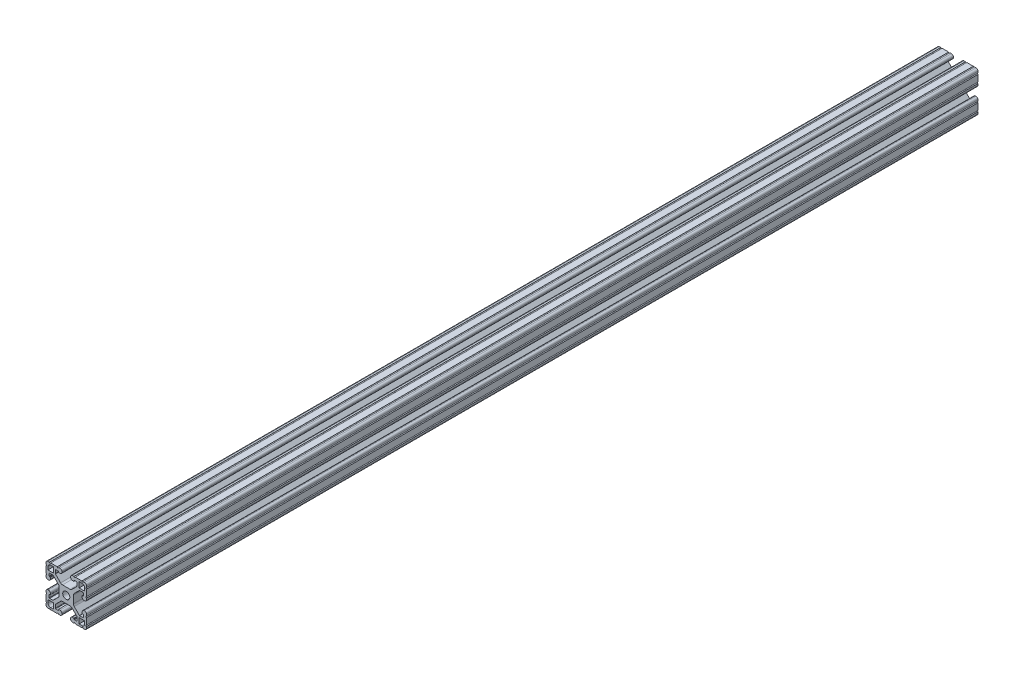
SolidWorks part; units mm, degrees
ref_plane "Front Plane" through (0, 0, 0) normal (0, 0, 1) x (1, 0, 0)
ref_plane "Top Plane" through (0, 0, 0) normal (0, 1, 0) x (1, 0, 0)
ref_plane "Right Plane" through (0, 0, 0) normal (1, 0, 0) x (0, 0, -1)
sketch "Sketch1" plane through (0, 0, 0) normal (0, 0, 1) x (1, 0, 0)
  line L0 (0, -19.05) -> (0, 19.05) construction
  line L1 (19.05, 0) -> (-19.05, 0) construction
  line L2 (4.064, 19.05) -> (-4.064, 19.05) construction
  line L3 (0, -6.7564) -> (0, 6.7564) construction
  line L4 (-4.064, 19.05) -> (-4.064, 14.986) construction
  line L5 (19.05, -10.287) -> (19.05, 10.287) construction
  line L6 (0, -3.3274) -> (0, 3.3274) construction
  line L7 (0, 0) -> (-19.05, 19.05) construction
  line L8 (-8.4474, 10.6026) -> (-10.6026, 8.4474) construction
  point P4 (0, 0)
  point P8 (0, 0)
  point P11 (0, 19.05)
  point P14 (0, 0)
  point P18 (19.05, 0)
  point P21 (0, 0)
  point P24 (-9.525, 9.525)
  point P26 (-9.525, 9.525)
  dimension "T-Slot Width" = 8.128
  dimension "Thickness" = 4.064
  dimension "Opening Width" = 20.574
  dimension "Slot Depth" = 12.2936
  dimension "Center Hole Diameter" = 6.6548
  dimension "Rail Height" = 38.1
  dimension "Rail Width" = 38.1
  dimension "D1" = 45
  dimension "Wall" = 3.048
sketch "Sketch2" plane through (0, 0, 0) normal (1, 0, 0) x (0, 0, -1)
  line L0 (-457.2, 0) -> (457.2, 0) construction
  line L1 (-381, -19.05) -> (-381, 19.05) construction
  line L2 (381, -19.05) -> (381, 19.05) construction
  line L3 (0, -19.05) -> (0, 19.05) construction
  point P4 (0, 0)
  point P7 (-381, 0)
  point P10 (381, 0)
  dimension "Length" = 914.4
  dimension "D1" = 76.2
  dimension "D2" = 76.2
sketch "Sketch3" plane through (0, 0, 0) normal (0, 0, 1) x (1, 0, 0)
  line L1 (19.05, -19.05) -> (-19.05, -19.05)
  line L2 (19.05, -19.05) -> (19.05, 19.05)
  line L3 (19.05, 19.05) -> (-19.05, 19.05)
  line L4 (-19.05, -19.05) -> (-19.05, 19.05)
  line L5 (19.05, -19.05) -> (-19.05, 19.05) construction
  line L6 (19.05, 19.05) -> (-19.05, -19.05) construction
  point P0 (0, 0)
extrude "Boss-Extrude1" add sketch "Sketch3" along normal blind 431.8 and the other way blind 406.4
sketch "Sketch4" plane through (0, 0, 431.8) normal (0, 0, 1) x (1, 0, 0)
  line L4 (4.064, 14.986) -> (4.064, 19.05)
  line L5 (7.239, 14.986) -> (4.064, 14.986)
  line L6 (19.05, 0) -> (-19.05, 0) construction
  line L7 (4.6011, 6.7564) -> (-4.6011, 6.7564)
  line L8 (-4.6011, 6.7564) -> (-10.287, 12.4423)
  line L37 (-19.05, 19.05) -> (-19.05, -19.05) construction
  line L38 (-19.05, -19.05) -> (19.05, -19.05) construction
  line L39 (-10.287, 12.4423) -> (-10.287, 16.002)
  line L40 (-10.287, 16.002) -> (-7.239, 16.002)
  line L41 (-7.239, 16.002) -> (-7.239, 14.986)
  line L42 (-7.239, 14.986) -> (-4.064, 14.986)
  line L43 (-4.064, 14.986) -> (-4.064, 19.05)
  line L44 (-4.064, 19.05) -> (4.064, 19.05)
  line L45 (0, 19.05) -> (0, 0) construction
  line L46 (-19.05, 19.05) -> (0, 0) construction
  line L47 (7.239, 16.002) -> (7.239, 14.986)
  line L48 (10.287, 16.002) -> (7.239, 16.002)
  line L49 (10.287, 12.4423) -> (10.287, 16.002)
  line L50 (4.6011, 6.7564) -> (10.287, 12.4423)
  line L51 (-19.05, 0) -> (19.05, 0) construction
  line L52 (4.6011, -6.7564) -> (10.287, -12.4423)
  line L53 (10.287, -12.4423) -> (10.287, -16.002)
  line L54 (10.287, -16.002) -> (7.239, -16.002)
  line L55 (7.239, -16.002) -> (7.239, -14.986)
  line L56 (-4.064, -19.05) -> (4.064, -19.05)
  line L57 (-4.064, -14.986) -> (-4.064, -19.05)
  line L58 (-7.239, -14.986) -> (-4.064, -14.986)
  line L59 (-7.239, -16.002) -> (-7.239, -14.986)
  line L60 (-10.287, -16.002) -> (-7.239, -16.002)
  line L61 (-10.287, -12.4423) -> (-10.287, -16.002)
  line L62 (-4.6011, -6.7564) -> (-10.287, -12.4423)
  line L63 (4.6011, -6.7564) -> (-4.6011, -6.7564)
  line L64 (7.239, -14.986) -> (4.064, -14.986)
  line L65 (4.064, -14.986) -> (4.064, -19.05)
  line L66 (-6.7564, -4.6011) -> (-12.4423, -10.287)
  line L67 (-12.4423, -10.287) -> (-16.002, -10.287)
  line L68 (-16.002, -10.287) -> (-16.002, -7.239)
  line L69 (-16.002, -7.239) -> (-14.986, -7.239)
  line L70 (-19.05, 4.064) -> (-19.05, -4.064)
  line L71 (-14.986, 4.064) -> (-19.05, 4.064)
  line L72 (-14.986, 7.239) -> (-14.986, 4.064)
  line L73 (-16.002, 7.239) -> (-14.986, 7.239)
  line L74 (-16.002, 10.287) -> (-16.002, 7.239)
  line L75 (-12.4423, 10.287) -> (-16.002, 10.287)
  line L76 (-6.7564, 4.6011) -> (-12.4423, 10.287)
  line L77 (-6.7564, -4.6011) -> (-6.7564, 4.6011)
  line L78 (-14.986, -7.239) -> (-14.986, -4.064)
  line L79 (-14.986, -4.064) -> (-19.05, -4.064)
  line L80 (14.986, -4.064) -> (19.05, -4.064)
  line L81 (14.986, -7.239) -> (14.986, -4.064)
  line L82 (6.7564, -4.6011) -> (6.7564, 4.6011)
  line L83 (6.7564, 4.6011) -> (12.4423, 10.287)
  line L84 (12.4423, 10.287) -> (16.002, 10.287)
  line L85 (16.002, 10.287) -> (16.002, 7.239)
  line L86 (16.002, 7.239) -> (14.986, 7.239)
  line L87 (14.986, 7.239) -> (14.986, 4.064)
  line L88 (14.986, 4.064) -> (19.05, 4.064)
  line L89 (19.05, 4.064) -> (19.05, -4.064)
  line L90 (16.002, -7.239) -> (14.986, -7.239)
  line L91 (16.002, -10.287) -> (16.002, -7.239)
  line L92 (12.4423, -10.287) -> (16.002, -10.287)
  line L93 (6.7564, -4.6011) -> (12.4423, -10.287)
  line L94 (19.05, -19.05) -> (19.05, 19.05) construction
  line L95 (12.065, 17.272) -> (17.272, 17.272)
  line L96 (12.065, 17.272) -> (12.065, 12.065)
  line L97 (12.065, 12.065) -> (17.272, 12.065)
  line L98 (17.272, 17.272) -> (17.272, 12.065)
  line L99 (19.05, 19.05) -> (-19.05, 19.05) construction
  line L100 (17.272, -17.272) -> (17.272, -12.065)
  line L101 (12.065, -17.272) -> (17.272, -17.272)
  line L102 (12.065, -17.272) -> (12.065, -12.065)
  line L103 (12.065, -12.065) -> (17.272, -12.065)
  line L104 (-17.272, 17.272) -> (-17.272, 12.065)
  line L105 (-12.065, 12.065) -> (-17.272, 12.065)
  line L106 (-12.065, 17.272) -> (-12.065, 12.065)
  line L107 (-12.065, 17.272) -> (-17.272, 17.272)
  line L108 (-12.065, -12.065) -> (-17.272, -12.065)
  line L109 (-12.065, -17.272) -> (-12.065, -12.065)
  line L110 (-12.065, -17.272) -> (-17.272, -17.272)
  line L111 (-17.272, -17.272) -> (-17.272, -12.065)
  circle A5 centre (0, 0) radius 3.3274
  point P21 (0, 6.7564)
  point P23 (0, -6.7564)
  point P38 (-6.7564, 0)
  point P53 (6.7564, 0)
  dimension "D1" = 20.574
  dimension "D3" = 3.048
  dimension "D4" = 3.048
  dimension "D5" = 1.778
  dimension "D6" = 1.778
  dimension "D7" = 1.778
extrude "Cut-Extrude1" cut sketch "Sketch4" against normal through all
sketch "Sketch5" plane through (0, 0, 431.8) normal (0, 0, 1) x (1, 0, 0)
  line L4 (-4.064, 19.05) -> (-19.05, 19.05) construction
  line L26 (-19.05, 19.05) -> (-19.05, 4.064) construction
  line L27 (-15.875, 19.05) -> (-14.605, 19.05)
  line L28 (-8.509, 19.05) -> (-7.239, 19.05)
  line L29 (-19.05, 15.875) -> (-19.05, 14.605)
  line L30 (-19.05, 8.509) -> (-19.05, 7.239)
  line L31 (8.509, 19.05) -> (7.239, 19.05)
  line L32 (15.875, 19.05) -> (14.605, 19.05)
  line L33 (19.05, 15.875) -> (19.05, 14.605)
  line L34 (19.05, 8.509) -> (19.05, 7.239)
  line L35 (19.05, -8.509) -> (19.05, -7.239)
  line L36 (19.05, -15.875) -> (19.05, -14.605)
  line L37 (15.875, -19.05) -> (14.605, -19.05)
  line L38 (8.509, -19.05) -> (7.239, -19.05)
  line L39 (-8.509, -19.05) -> (-7.239, -19.05)
  line L40 (-15.875, -19.05) -> (-14.605, -19.05)
  line L41 (-19.05, -15.875) -> (-19.05, -14.605)
  line L42 (-19.05, -8.509) -> (-19.05, -7.239)
  line L43 (19.05, 19.05) -> (4.064, 19.05) construction
  line L44 (19.05, 4.064) -> (19.05, 19.05) construction
  line L48 (-14.986, 4.064) -> (-19.05, 4.064) construction
  line L49 (-4.064, 14.986) -> (-4.064, 19.05) construction
  arc A8 (-15.875, 19.05) -> (-14.605, 19.05) centre (-15.24, 19.05) ccw
  arc A9 (-8.509, 19.05) -> (-7.239, 19.05) centre (-7.874, 19.05) ccw
  arc A10 (-19.05, 14.605) -> (-19.05, 15.875) centre (-19.05, 15.24) ccw
  arc A11 (-19.05, 7.239) -> (-19.05, 8.509) centre (-19.05, 7.874) ccw
  arc A12 (7.239, 19.05) -> (8.509, 19.05) centre (7.874, 19.05) ccw
  arc A13 (14.605, 19.05) -> (15.875, 19.05) centre (15.24, 19.05) ccw
  arc A14 (19.05, 15.875) -> (19.05, 14.605) centre (19.05, 15.24) ccw
  arc A15 (19.05, 8.509) -> (19.05, 7.239) centre (19.05, 7.874) ccw
  arc A16 (19.05, -7.239) -> (19.05, -8.509) centre (19.05, -7.874) ccw
  arc A17 (19.05, -14.605) -> (19.05, -15.875) centre (19.05, -15.24) ccw
  arc A18 (15.875, -19.05) -> (14.605, -19.05) centre (15.24, -19.05) ccw
  arc A19 (8.509, -19.05) -> (7.239, -19.05) centre (7.874, -19.05) ccw
  arc A20 (-7.239, -19.05) -> (-8.509, -19.05) centre (-7.874, -19.05) ccw
  arc A21 (-14.605, -19.05) -> (-15.875, -19.05) centre (-15.24, -19.05) ccw
  arc A22 (-19.05, -15.875) -> (-19.05, -14.605) centre (-19.05, -15.24) ccw
  arc A23 (-19.05, -8.509) -> (-19.05, -7.239) centre (-19.05, -7.874) ccw
  dimension "D2" = 0.635
  dimension "D4" = 3.81
  dimension "D5" = 3.81
  dimension "D1" = 3.81
  dimension "D3" = 3.81
  dimension "D7" = 4
extrude "Cut-Extrude2" cut sketch "Sketch5" against normal through all
fillet "Fillet1" radius 2.54 12 edges at (-6.7564, 4.6011, 12.7) (-6.7564, -4.6011, 12.7) (4.6011, -6.7564, 12.7) (-4.6011, -6.7564, 12.7) (6.7564, -4.6011, 12.7) (6.7564, 4.6011, 12.7) (4.6011, 6.7564, 12.7) (-4.6011, 6.7564, 12.7) (-17.272, 17.272, 12.7) (17.272, 17.272, 12.7) (17.272, -17.272, 12.7) (-17.272, -17.272, 12.7)
fillet "Fillet2" radius 1.778 20 edges at (19.05, -19.05, 12.7) (19.05, 19.05, 12.7) (-19.05, -19.05, 12.7) (-19.05, 19.05, 12.7) (-14.986, 4.064, 12.7) (-19.05, 4.064, 12.7) (-19.05, -4.064, 12.7) (-14.986, -4.064, 12.7) (-4.064, -19.05, 12.7) (-4.064, -14.986, 12.7) (4.064, -14.986, 12.7) (4.064, -19.05, 12.7) (19.05, -4.064, 12.7) (14.986, -4.064, 12.7) (19.05, 4.064, 12.7) (14.986, 4.064, 12.7) (4.064, 14.986, 12.7) (4.064, 19.05, 12.7) (-4.064, 19.05, 12.7) (-4.064, 14.986, 12.7)
fillet "Fillet3" radius 0.3969 24 edges at (-14.986, -7.239, 12.7) (-16.002, -10.287, 12.7) (-12.4423, -10.287, 12.7) (-12.4423, 10.287, 12.7) (-16.002, 7.239, 12.7) (-16.002, 10.287, 12.7) (-10.287, 12.4423, 12.7) (-7.239, 16.002, 12.7) (-10.287, 16.002, 12.7) (10.287, 16.002, 12.7) (7.239, 16.002, 12.7) (10.287, 12.4423, 12.7) (16.002, 10.287, 12.7) (12.4423, 10.287, 12.7) (16.002, 7.239, 12.7) (16.002, -7.239, 12.7) (16.002, -10.287, 12.7) (12.4423, -10.287, 12.7) (10.287, -12.4423, 12.7) (10.287, -16.002, 12.7) (7.239, -16.002, 12.7) (-7.239, -16.002, 12.7) (-10.287, -12.4423, 12.7) (-10.287, -16.002, 12.7)
equation "\"D4@Sketch5\"=\"D3@Sketch5\""
equation "\"D5@Sketch5\"=\"D4@Sketch5\""
equation "\"D1@Sketch4\"=\"Opening Width@Sketch1\""
equation "\"D2@Sketch2\"=\"D1@Sketch2\""
